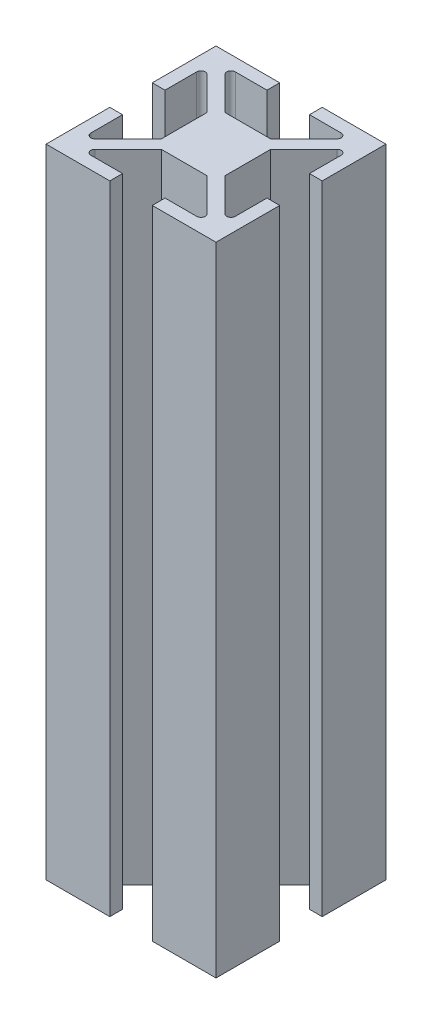
SolidWorks part; units mm, degrees
ref_plane "Plan de face" through (0, 0, 0) normal (0, 0, 1) x (1, 0, 0)
ref_plane "Plan de dessus" through (0, 0, 0) normal (0, 1, 0) x (1, 0, 0)
ref_plane "Plan de droite" through (0, 0, 0) normal (1, 0, 0) x (0, 0, -1)
sketch "Esquisse1" plane through (0, 0, 0) normal (0, 1, 0) x (1, 0, 0)
  line L0 (6.1245, 16.1036) -> (30.6226, 16.1036) construction
  line L6 (-11.5924, 0) -> (12.1076, 0) construction
  line L7 (0, 12.3466) -> (0, -12.7449) construction
  line L12 (-10, -10) -> (10, 10) construction
  line L59 (-10, -2.5) -> (-10, -10)
  line L60 (-10, -2.5) -> (-8.5, -2.5)
  line L69 (-8.5, -2.5) -> (-8.5, -6.2322)
  line L70 (-7.6464, -6.5858) -> (-3.75, -2.6893)
  line L73 (-6.5858, -7.6464) -> (-2.6893, -3.75)
  line L74 (-2.5, -8.5) -> (-6.2322, -8.5)
  line L75 (-2.5, -10) -> (-2.5, -8.5)
  line L76 (-2.5, -10) -> (-10, -10)
  line L77 (-2.5, 10) -> (-2.5, 8.5)
  line L78 (-2.5, 10) -> (-10, 10)
  line L79 (-10, 2.5) -> (-10, 10)
  line L80 (-10, 2.5) -> (-8.5, 2.5)
  line L81 (-8.5, 2.5) -> (-8.5, 6.2322)
  line L82 (-7.6464, 6.5858) -> (-3.75, 2.6893)
  line L83 (-6.5858, 7.6464) -> (-2.6893, 3.75)
  line L84 (-2.5, 8.5) -> (-6.2322, 8.5)
  line L85 (10, 2.5) -> (8.5, 2.5)
  line L86 (10, 2.5) -> (10, 10)
  line L87 (2.5, 10) -> (10, 10)
  line L88 (2.5, 10) -> (2.5, 8.5)
  line L89 (2.5, 8.5) -> (6.2322, 8.5)
  line L90 (6.5858, 7.6464) -> (2.6893, 3.75)
  line L91 (7.6464, 6.5858) -> (3.75, 2.6893)
  line L92 (8.5, 2.5) -> (8.5, 6.2322)
  line L93 (2.5, -10) -> (2.5, -8.5)
  line L94 (2.5, -10) -> (10, -10)
  line L95 (10, -2.5) -> (10, -10)
  line L96 (10, -2.5) -> (8.5, -2.5)
  line L97 (8.5, -2.5) -> (8.5, -6.2322)
  line L98 (7.6464, -6.5858) -> (3.75, -2.6893)
  line L99 (6.5858, -7.6464) -> (2.6893, -3.75)
  line L100 (2.5, -8.5) -> (6.2322, -8.5)
  line L101 (-3.75, 2.6893) -> (-3.75, -2.6893)
  line L102 (-2.6893, -3.75) -> (2.6893, -3.75)
  line L103 (-2.6893, 3.75) -> (2.6893, 3.75)
  line L104 (3.75, 2.6893) -> (3.75, -2.6893)
  arc A0 (-8.5, 6.2322) -> (-7.6464, 6.5858) centre (-8, 6.2322) cw
  arc A1 (-8.5, -6.2322) -> (-7.6464, -6.5858) centre (-8, -6.2322) ccw
  arc A2 (-6.5858, -7.6464) -> (-6.2322, -8.5) centre (-6.2322, -8) ccw
  arc A3 (6.5858, -7.6464) -> (6.2322, -8.5) centre (6.2322, -8) cw
  arc A4 (8.5, -6.2322) -> (7.6464, -6.5858) centre (8, -6.2322) cw
  arc A5 (7.6464, 6.5858) -> (8.5, 6.2322) centre (8, 6.2322) cw
  arc A6 (6.2322, 8.5) -> (6.5858, 7.6464) centre (6.2322, 8) cw
  arc A7 (-6.5858, 7.6464) -> (-6.2322, 8.5) centre (-6.2322, 8) cw
  point P7 (-2.5, -9.25)
  point P8 (2.5, -9.25)
  point P15 (-8.5, -7.4393)
  point P51 (0, 0)
  point P52 (-7.4393, -8.5)
  dimension "D2" = 5
  dimension "D7" = 0.5
  dimension "D1" = 20
  dimension "D3" = 4
  dimension "D4" = 7.5
  dimension "D5" = 1.5
  dimension "D6" = 1.5
extrude "Boss.-Extru.1" add sketch "Esquisse1" along normal blind 75
